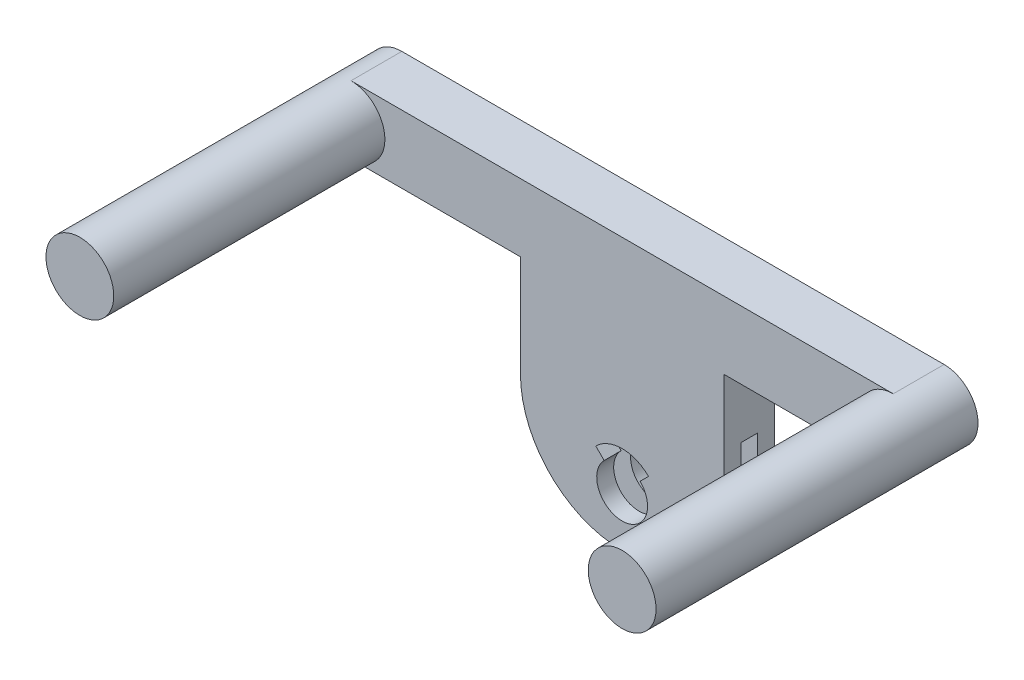
SolidWorks part; units mm, degrees
ref_plane "前视基准面" through (0, 0, 0) normal (0, 0, 1) x (1, 0, 0)
ref_plane "上视基准面" through (0, 0, 0) normal (0, 1, 0) x (1, 0, 0)
ref_plane "右视基准面" through (0, 0, 0) normal (1, 0, 0) x (0, 0, -1)
other "Configuration Table"
sketch "草图1" plane through (0, 0, 0) normal (0, 0, 1) x (1, 0, 0)
  line L0 (-197.7114, 114.3288) -> (122.2886, 114.3288)
  line L1 (122.2886, 114.3288) -> (122.2886, 74.3288)
  line L2 (122.2886, 74.3288) -> (22.2886, 74.3288)
  line L3 (22.2886, 74.3288) -> (22.2886, 14.3288)
  line L4 (22.2886, 14.3288) -> (-97.7114, 14.3288)
  line L5 (-97.7114, 14.3288) -> (-97.7114, 74.3288)
  line L6 (-97.7114, 74.3288) -> (-197.7114, 74.3288)
  line L7 (-197.7114, 74.3288) -> (-197.7114, 114.3288)
  circle A0 centre (-197.7114, 94.3288) radius 20
  circle A1 centre (122.2886, 94.3288) radius 20
  dimension "D6" = 90
  dimension "D1" = 320
  dimension "D2" = 40
  dimension "D3" = 100
  dimension "D4" = 100
  dimension "D5" = 60
extrude "凸台-拉伸1" add sketch "草图1" along normal blind 30 contours A1 L0 A0 L6 L5 L4 L3 L2 | L1 A1 | L1 A1
sketch "草图3" plane through (0, 0, 0) normal (0, 0, -1) x (-1, 0, 0)
  line L0 (-22.2886, 14.3288) -> (97.7114, 14.3288)
  circle A0 centre (37.7114, 14.3288) radius 60
  line M4 (-22.2886, 14.3288) -> (97.7114, 14.3288)
extrude "凸台-拉伸2" add sketch "草图3" against normal blind 10 contours A0 M4
sketch "草图4" plane through (0, 0, 30) normal (0, 0, 1) x (1, 0, 0)
  line L0 (-97.7114, 14.3288) -> (22.2886, 14.3288)
  circle A0 centre (-37.7114, 14.3288) radius 60
  line M8 (-97.7114, 14.3288) -> (22.2886, 14.3288)
extrude "凸台-拉伸3" add sketch "草图4" against normal blind 10 contours A0 M8
sketch "草图5" plane through (0, 0, 30) normal (0, 0, 1) x (1, 0, 0)
  line L0 (-97.7114, 14.3288) -> (22.2886, 14.3288)
  line L1 (-37.7114, 14.3288) -> (-37.7114, -15.6712)
  line L2 (-37.7114, -15.6712) -> (-67.7114, 14.3288)
  line L3 (-37.7114, -15.6712) -> (-7.7114, 14.3288)
  circle A0 centre (-37.7114, -15.6712) radius 15
  circle A1 centre (-37.7114, -15.6712) radius 22
  dimension "D1" = 45
  dimension "D3" = 44
  dimension "D4" = 30
  dimension "D2" = 45
  dimension "D5" = 30
extrude "切除-拉伸1" cut sketch "草图5" against normal blind 30 contours L1 A1 L2 A0 | L3 A1 L1 A0 | L3 A0 L1 | L1 A0 L2 | L2 A0 L3
sketch "草图6" plane through (0, 14.3288, 0) normal (0, -1, 0) x (1, 0, 0)
  line L0 (-97.7114, 20) -> (22.2886, 20)
  line L1 (22.2886, 20) -> (22.2886, 10)
  line L2 (22.2886, 30) -> (22.2886, 0) construction
  line L3 (22.2886, 20) -> (22.2886, 10) construction
  line L4 (22.2886, 10) -> (-97.7114, 10)
  line L5 (-97.7114, 10) -> (-97.7114, 20)
extrude "切除-拉伸2" cut sketch "草图6" against normal blind 20
sketch "草图7" plane through (0, 0, 30) normal (0, 0, 1) x (1, 0, 0)
  circle A0 centre (-197.7114, 94.3288) radius 20
  circle A1 centre (122.2886, 94.3288) radius 20
extrude "凸台-拉伸4" add sketch "草图7" along normal blind 160
